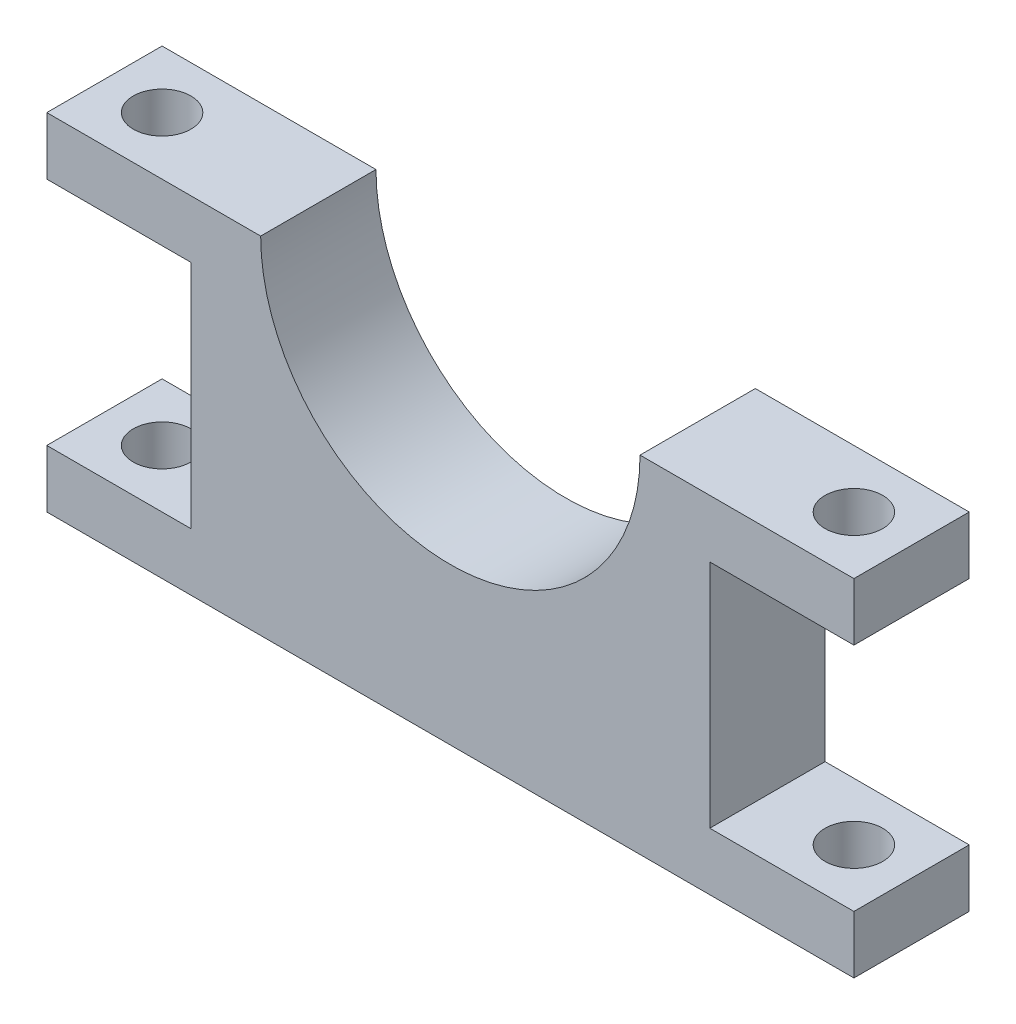
SolidWorks part; units mm, degrees
ref_plane "前视基准面" through (0, 0, 0) normal (0, 0, 1) x (1, 0, 0)
ref_plane "上视基准面" through (0, 0, 0) normal (0, 1, 0) x (1, 0, 0)
ref_plane "右视基准面" through (0, 0, 0) normal (1, 0, 0) x (0, 0, -1)
sketch "草图1" plane through (0, 0, 0) normal (0, 0, 1) x (1, 0, 0)
  line L0 (16.45, 0) -> (22.5, 0)
  line L1 (22.5, 0) -> (22.5, -30)
  line L2 (22.5, -30) -> (-22.5, -30)
  line L3 (0, 0) -> (0, -12.6404) construction
  line L4 (-22.5, 0) -> (-22.5, -30)
  line L5 (-16.45, 0) -> (-22.5, 0)
  arc A0 (-16.45, 0) -> (16.45, 0) centre (0, 0) ccw
  point P9 (0, -30)
  dimension "D1" = 32.9
  dimension "D2" = 45
  dimension "D3" = 30
extrude "凸台-拉伸1" add sketch "草图1" along normal mid plane 10
sketch "草图3" plane through (0, -30, 0) normal (0, -1, 0) x (1, 0, 0)
  line L1 (-35, 5) -> (35, 5)
  line L2 (-35, 5) -> (-35, -5)
  line L3 (-35, -5) -> (35, -5)
  line L4 (35, 5) -> (35, -5)
  line L5 (0, -5) -> (0, 5) construction
  line L6 (-35, 0) -> (35, 0) construction
  circle A0 centre (-30, 0) radius 2.5
  circle A1 centre (30, 0) radius 2.5
  point P0 (0, 0)
  dimension "D2" = 5
  dimension "D1" = 10
  dimension "D3" = 30
  dimension "D4" = 70
extrude "凸台-拉伸2" add sketch "草图3" against normal blind 5
sketch "草图4" plane through (0, 0, 0) normal (0, 1, 0) x (1, 0, 0)
  line L0 (-22.5, 5) -> (-22.5, -5)
  line L1 (-35, 5) -> (-22.5, 5)
  line L2 (-35, 5) -> (-35, -5)
  line L3 (-35, -5) -> (-22.5, -5)
  line L4 (35, 5) -> (35, -5)
  line L5 (0, -5) -> (0, 5) construction
  line L6 (-35, 0) -> (-22.5, 0) construction
  line L7 (22.5, 5) -> (22.5, -5)
  line L8 (22.5, 5) -> (35, 5)
  line L9 (22.5, 0) -> (35, 0) construction
  line L10 (22.5, -5) -> (35, -5)
  circle A0 centre (-30, 0) radius 2.5
  circle A1 centre (30, 0) radius 2.5
  point P0 (0, 0)
extrude "凸台-拉伸3" add sketch "草图4" against normal blind 5
